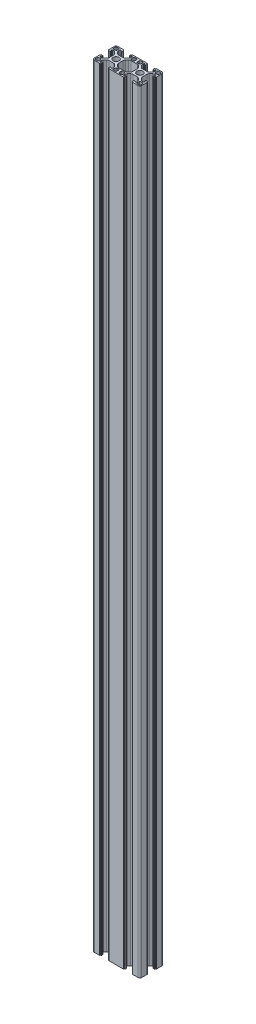
SolidWorks part; units mm, degrees
ref_plane "Спереди" through (0, 0, 0) normal (0, 0, 1) x (1, 0, 0)
ref_plane "Сверху" through (0, 0, 0) normal (0, 1, 0) x (1, 0, 0)
ref_plane "Справа" through (0, 0, 0) normal (1, 0, 0) x (0, 0, -1)
sketch "Эскиз1" plane through (0, 0, 0) normal (0, 1, 0) x (1, 0, 0)
  line L0 (-3.1522, 8.2837) -> (-1.6522, 6.7837) construction
  line L1 (18.3478, 9.7837) -> (15.3478, 6.7837) construction
  line L2 (-10.7522, 0.6837) -> (-0.7522, 10.6837) construction
  line L3 (9.2478, 4.6837) -> (11.1466, 4.6837)
  line L4 (9.2478, 0.6837) -> (19.2478, 10.6837) construction
  line L5 (16.8478, 8.2837) -> (15.3478, 9.7837) construction
  line L6 (12.5608, 5.2695) -> (13.862, 6.5707)
  line L7 (16.1478, 6.7837) -> (17.5478, 6.7837)
  line L8 (15.3478, 7.5837) -> (15.3478, 8.9837)
  line L9 (17.5478, 9.7837) -> (16.1478, 9.7837)
  line L10 (14.4478, 8.8837) -> (14.4478, 7.9849)
  line L11 (13.011, 8.757) -> (13.4914, 9.2373)
  line L12 (12.4478, 10.2328) -> (12.9478, 10.2328)
  line L13 (12.8343, 8.6837) -> (12.5478, 8.6837)
  line L14 (13.8449, 9.3837) -> (13.9478, 9.3837)
  line L15 (12.9478, 10.5337) -> (12.9478, 10.2328)
  line L16 (12.2978, 10.0828) -> (12.2978, 8.9337)
  line L17 (17.7478, 10.6837) -> (13.0978, 10.6837)
  line L18 (18.3478, 8.9837) -> (18.3478, 7.5837)
  line L19 (19.2478, 9.1837) -> (19.2478, 4.5337)
  line L20 (18.6469, 3.7337) -> (17.4978, 3.7337)
  line L21 (19.0978, 4.3837) -> (18.7969, 4.3837)
  line L22 (17.9478, 5.2808) -> (17.9478, 5.3837)
  line L23 (17.2478, 4.2702) -> (17.2478, 3.9837)
  line L24 (18.7969, 3.8837) -> (18.7969, 4.3837)
  line L25 (17.321, 4.447) -> (17.8014, 4.9273)
  line L26 (17.4478, 5.8837) -> (16.549, 5.8837)
  line L27 (13.8336, 3.9967) -> (15.1348, 5.2979)
  line L28 (13.2478, 0.6837) -> (13.2478, 2.5825)
  line L29 (13.2478, 0.6837) -> (13.2478, -1.2151)
  line L30 (13.8336, -2.6293) -> (15.1348, -3.9305)
  line L31 (15.3478, -6.2163) -> (15.3478, -7.6163)
  line L32 (16.1478, -5.4163) -> (17.5478, -5.4163)
  line L33 (18.3478, -7.6163) -> (18.3478, -6.2163)
  line L34 (17.4478, -4.5163) -> (16.549, -4.5163)
  line L35 (17.321, -3.0795) -> (17.8014, -3.5598)
  line L36 (18.7969, -2.5163) -> (18.7969, -3.0163)
  line L37 (17.2478, -2.9027) -> (17.2478, -2.6163)
  line L38 (17.9478, -3.9134) -> (17.9478, -4.0163)
  line L39 (19.0978, -3.0163) -> (18.7969, -3.0163)
  line L40 (18.6469, -2.3663) -> (17.4978, -2.3663)
  line L41 (19.2478, -7.8163) -> (19.2478, -3.1663)
  line L42 (17.5478, -8.4163) -> (16.1478, -8.4163)
  line L43 (17.7478, -9.3163) -> (13.0978, -9.3163)
  line L44 (12.2978, -8.7153) -> (12.2978, -7.5663)
  line L45 (12.9478, -9.1663) -> (12.9478, -8.8653)
  line L46 (13.8449, -8.0163) -> (13.9478, -8.0163)
  line L47 (12.8343, -7.3163) -> (12.5478, -7.3163)
  line L48 (12.4478, -8.8653) -> (12.9478, -8.8653)
  line L49 (13.011, -7.3895) -> (13.4914, -7.8698)
  line L50 (14.4478, -7.5163) -> (14.4478, -6.6175)
  line L51 (12.5608, -3.9021) -> (13.862, -5.2033)
  line L52 (9.2478, -3.3163) -> (11.1466, -3.3163)
  line L53 (18.3478, -8.4163) -> (15.3478, -5.4163) construction
  line L54 (9.2478, 0.6837) -> (19.2478, -9.3163) construction
  line L55 (16.8478, -6.9163) -> (18.3478, -5.4163) construction
  line L56 (9.2478, -3.3163) -> (7.349, -3.3163)
  line L57 (5.9348, -3.9021) -> (4.6336, -5.2033)
  line L58 (2.3478, -5.4163) -> (0.9478, -5.4163)
  line L59 (3.1478, -6.2163) -> (3.1478, -7.6163)
  line L60 (0.9478, -8.4163) -> (2.3478, -8.4163)
  line L61 (4.0478, -7.5163) -> (4.0478, -6.6175)
  line L62 (5.4846, -7.3895) -> (5.0043, -7.8698)
  line L63 (6.0478, -8.8653) -> (5.5478, -8.8653)
  line L64 (5.6614, -7.3163) -> (5.9478, -7.3163)
  line L65 (4.6507, -8.0163) -> (4.5478, -8.0163)
  line L66 (5.5478, -9.1663) -> (5.5478, -8.8653)
  line L67 (6.1978, -8.7153) -> (6.1978, -7.5663)
  line L68 (0.7478, -9.3163) -> (5.3978, -9.3163)
  line L69 (0.1478, -7.6163) -> (0.1478, -6.2163)
  line L70 (1.0478, -4.5163) -> (1.9466, -4.5163)
  line L71 (4.662, -2.6293) -> (3.3608, -3.9305)
  line L72 (5.2478, 0.6837) -> (5.2478, -1.2151)
  line L73 (-1.6522, 9.7837) -> (-4.6522, 6.7837) construction
  line L74 (0.1478, -8.4163) -> (3.1478, -5.4163) construction
  line L75 (-3.1522, -6.9163) -> (-4.6522, -8.4163) construction
  line L76 (9.2478, 0.6837) -> (-0.7522, -9.3163) construction
  line L77 (1.6478, -6.9163) -> (3.1478, -8.4163) construction
  line L78 (5.2478, 0.6837) -> (5.2478, 2.5825)
  line L79 (4.662, 3.9967) -> (3.3608, 5.2979)
  line L80 (3.1478, 7.5837) -> (3.1478, 8.9837)
  line L81 (2.3478, 6.7837) -> (0.9478, 6.7837)
  line L82 (0.1478, 8.9837) -> (0.1478, 7.5837)
  line L83 (1.0478, 5.8837) -> (1.9466, 5.8837)
  line L84 (0.9478, 9.7837) -> (2.3478, 9.7837)
  line L85 (0.7478, 10.6837) -> (5.3978, 10.6837)
  line L86 (6.1978, 10.0828) -> (6.1978, 8.9337)
  line L87 (5.5478, 10.5337) -> (5.5478, 10.2328)
  line L88 (4.6507, 9.3837) -> (4.5478, 9.3837)
  line L89 (5.6614, 8.6837) -> (5.9478, 8.6837)
  line L90 (6.0478, 10.2328) -> (5.5478, 10.2328)
  line L91 (5.4846, 8.757) -> (5.0043, 9.2373)
  line L92 (4.0478, 8.8837) -> (4.0478, 7.9849)
  line L93 (5.9348, 5.2695) -> (4.6336, 6.5707)
  line L94 (9.2478, 4.6837) -> (7.349, 4.6837)
  line L95 (-2.5162, 0.6837) -> (20.7522, 0.6837) construction
  line L96 (0.1478, 9.7837) -> (3.1478, 6.7837) construction
  line L97 (9.2478, -11.4027) -> (9.2478, 11.4027) construction
  line L98 (9.2478, 0.6837) -> (-0.7522, 10.6837) construction
  line L99 (1.6478, 8.2837) -> (0.1478, 6.7837) construction
  line L100 (-10.7522, 0.6837) -> (-0.7522, -9.3163) construction
  line L101 (-1.6522, -8.4163) -> (-4.6522, -5.4163) construction
  line L102 (-18.3522, -6.9163) -> (-19.8522, -5.4163) construction
  line L103 (-10.7522, 0.6837) -> (-20.7522, -9.3163) construction
  line L104 (-19.8522, -8.4163) -> (-16.8522, -5.4163) construction
  line L105 (-18.3522, 8.2837) -> (-16.8522, 9.7837) construction
  line L106 (-10.7522, 0.6837) -> (-20.7522, 10.6837) construction
  line L107 (-19.8522, 9.7837) -> (-16.8522, 6.7837) construction
  line L108 (-10.7522, 4.6837) -> (-8.8534, 4.6837)
  line L109 (-7.4392, 5.2695) -> (-6.138, 6.5707)
  line L110 (-5.5522, 8.8837) -> (-5.5522, 7.9849)
  line L111 (-6.989, 8.757) -> (-6.5086, 9.2373)
  line L112 (-7.5522, 10.2328) -> (-7.0522, 10.2328)
  line L113 (-7.1657, 8.6837) -> (-7.4522, 8.6837)
  line L114 (-6.1551, 9.3837) -> (-6.0522, 9.3837)
  line L115 (-7.0522, 10.5337) -> (-7.0522, 10.2328)
  line L116 (-7.7022, 10.0828) -> (-7.7022, 8.9337)
  line L117 (-2.2522, 10.6837) -> (-6.9022, 10.6837)
  line L118 (-2.4522, 9.7837) -> (-3.8522, 9.7837)
  line L119 (-2.5522, 5.8837) -> (-3.451, 5.8837)
  line L120 (-1.6522, 8.9837) -> (-1.6522, 7.5837)
  line L121 (-3.8522, 6.7837) -> (-2.4522, 6.7837)
  line L122 (-4.6522, 7.5837) -> (-4.6522, 8.9837)
  line L123 (-6.1664, 3.9967) -> (-4.8652, 5.2979)
  line L124 (-6.7522, 0.6837) -> (-6.7522, 2.5825)
  line L125 (-6.7522, 0.6837) -> (-6.7522, -1.2151)
  line L126 (-6.1664, -2.6293) -> (-4.8652, -3.9305)
  line L127 (-2.5522, -4.5163) -> (-3.451, -4.5163)
  line L128 (-1.6522, -7.6163) -> (-1.6522, -6.2163)
  line L129 (-2.2522, -9.3163) -> (-6.9022, -9.3163)
  line L130 (-7.7022, -8.7153) -> (-7.7022, -7.5663)
  line L131 (-7.0522, -9.1663) -> (-7.0522, -8.8653)
  line L132 (-6.1551, -8.0163) -> (-6.0522, -8.0163)
  line L133 (-7.1657, -7.3163) -> (-7.4522, -7.3163)
  line L134 (-7.5522, -8.8653) -> (-7.0522, -8.8653)
  line L135 (-6.989, -7.3895) -> (-6.5086, -7.8698)
  line L136 (-5.5522, -7.5163) -> (-5.5522, -6.6175)
  line L137 (-2.4522, -8.4163) -> (-3.8522, -8.4163)
  line L138 (-4.6522, -6.2163) -> (-4.6522, -7.6163)
  line L139 (-3.8522, -5.4163) -> (-2.4522, -5.4163)
  line L140 (-7.4392, -3.9021) -> (-6.138, -5.2033)
  line L141 (-10.7522, -3.3163) -> (-8.8534, -3.3163)
  line L142 (-10.7522, -3.3163) -> (-12.651, -3.3163)
  line L143 (-14.0652, -3.9021) -> (-15.3664, -5.2033)
  line L144 (-15.9522, -7.5163) -> (-15.9522, -6.6175)
  line L145 (-14.5154, -7.3895) -> (-14.9957, -7.8698)
  line L146 (-13.9522, -8.8653) -> (-14.4522, -8.8653)
  line L147 (-14.3386, -7.3163) -> (-14.0522, -7.3163)
  line L148 (-15.3493, -8.0163) -> (-15.4522, -8.0163)
  line L149 (-14.4522, -9.1663) -> (-14.4522, -8.8653)
  line L150 (-13.8022, -8.7153) -> (-13.8022, -7.5663)
  line L151 (-19.2522, -9.3163) -> (-14.6022, -9.3163)
  line L152 (-19.0522, -8.4163) -> (-17.6522, -8.4163)
  line L153 (-20.7522, -7.8163) -> (-20.7522, -3.1663)
  line L154 (-20.1512, -2.3663) -> (-19.0022, -2.3663)
  line L155 (-20.6022, -3.0163) -> (-20.3012, -3.0163)
  line L156 (-19.4522, -3.9134) -> (-19.4522, -4.0163)
  line L157 (-18.7522, -2.9027) -> (-18.7522, -2.6163)
  line L158 (-20.3012, -2.5163) -> (-20.3012, -3.0163)
  line L159 (-18.8254, -3.0795) -> (-19.3057, -3.5598)
  line L160 (-18.9522, -4.5163) -> (-18.0534, -4.5163)
  line L161 (-19.8522, -7.6163) -> (-19.8522, -6.2163)
  line L162 (-17.6522, -5.4163) -> (-19.0522, -5.4163)
  line L163 (-16.8522, -6.2163) -> (-16.8522, -7.6163)
  line L164 (-15.338, -2.6293) -> (-16.6392, -3.9305)
  line L165 (-14.7522, 0.6837) -> (-14.7522, -1.2151)
  line L166 (-14.7522, 0.6837) -> (-14.7522, 2.5825)
  line L167 (-15.338, 3.9967) -> (-16.6392, 5.2979)
  line L168 (-18.9522, 5.8837) -> (-18.0534, 5.8837)
  line L169 (-18.8254, 4.447) -> (-19.3057, 4.9273)
  line L170 (-20.3012, 3.8837) -> (-20.3012, 4.3837)
  line L171 (-18.7522, 4.2702) -> (-18.7522, 3.9837)
  line L172 (-19.4522, 5.2808) -> (-19.4522, 5.3837)
  line L173 (-20.6022, 4.3837) -> (-20.3012, 4.3837)
  line L174 (-20.1512, 3.7337) -> (-19.0022, 3.7337)
  line L175 (-20.7522, 9.1837) -> (-20.7522, 4.5337)
  line L176 (-19.8522, 8.9837) -> (-19.8522, 7.5837)
  line L177 (-19.2522, 10.6837) -> (-14.6022, 10.6837)
  line L178 (-13.8022, 10.0828) -> (-13.8022, 8.9337)
  line L179 (-14.4522, 10.5337) -> (-14.4522, 10.2328)
  line L180 (-15.3493, 9.3837) -> (-15.4522, 9.3837)
  line L181 (-14.3386, 8.6837) -> (-14.0522, 8.6837)
  line L182 (-13.9522, 10.2328) -> (-14.4522, 10.2328)
  line L183 (-14.5154, 8.757) -> (-14.9957, 9.2373)
  line L184 (-15.9522, 8.8837) -> (-15.9522, 7.9849)
  line L185 (-19.0522, 9.7837) -> (-17.6522, 9.7837)
  line L186 (-16.8522, 7.5837) -> (-16.8522, 8.9837)
  line L187 (-17.6522, 6.7837) -> (-19.0522, 6.7837)
  line L188 (-14.0652, 5.2695) -> (-15.3664, 6.5707)
  line L189 (-10.7522, 4.6837) -> (-12.651, 4.6837)
  line L190 (-2.2522, -9.3163) -> (0.7478, -9.3163)
  line L191 (-2.5522, -4.5163) -> (1.0478, -4.5163)
  line L192 (-2.5522, 5.8837) -> (1.0478, 5.8837)
  line L193 (-2.2522, 10.6837) -> (0.7478, 10.6837)
  arc A0 (18.3478, 8.9837) -> (17.5478, 9.7837) centre (17.5478, 8.9837) ccw
  arc A1 (16.1478, 9.7837) -> (15.3478, 8.9837) centre (16.1478, 8.9837) ccw
  arc A2 (16.1478, 6.7837) -> (15.3478, 7.5837) centre (16.1478, 7.5837) cw
  arc A3 (17.7478, 10.6837) -> (19.2478, 9.1837) centre (17.7478, 9.1837) cw
  arc A4 (12.4478, 10.2328) -> (12.2978, 10.0828) centre (12.4478, 10.0828) ccw
  arc A5 (13.0978, 10.6837) -> (12.9478, 10.5337) centre (13.0978, 10.5337) ccw
  arc A6 (12.8343, 8.6837) -> (13.011, 8.757) centre (12.8343, 8.9337) ccw
  arc A7 (12.5478, 8.6837) -> (12.2978, 8.9337) centre (12.5478, 8.9337) cw
  arc A8 (13.4914, 9.2373) -> (13.8449, 9.3837) centre (13.8449, 8.8837) cw
  arc A9 (13.9478, 9.3837) -> (14.4478, 8.8837) centre (13.9478, 8.8837) cw
  arc A10 (11.7478, 0.6837) -> (9.2478, 3.1837) centre (9.2478, 0.6837) ccw
  arc A11 (11.1466, 4.6837) -> (12.5608, 5.2695) centre (11.1466, 6.6837) ccw
  arc A12 (14.4478, 7.9849) -> (13.862, 6.5707) centre (12.4478, 7.9849) cw
  arc A13 (18.3478, 7.5837) -> (17.5478, 6.7837) centre (17.5478, 7.5837) cw
  arc A14 (17.9478, 5.3837) -> (17.4478, 5.8837) centre (17.4478, 5.3837) ccw
  arc A15 (17.8014, 4.9273) -> (17.9478, 5.2808) centre (17.4478, 5.2808) ccw
  arc A16 (17.2478, 3.9837) -> (17.4978, 3.7337) centre (17.4978, 3.9837) ccw
  arc A17 (17.2478, 4.2702) -> (17.321, 4.447) centre (17.4978, 4.2702) cw
  arc A18 (19.2478, 4.5337) -> (19.0978, 4.3837) centre (19.0978, 4.5337) cw
  arc A19 (18.7969, 3.8837) -> (18.6469, 3.7337) centre (18.6469, 3.8837) cw
  arc A20 (16.549, 5.8837) -> (15.1348, 5.2979) centre (16.549, 3.8837) ccw
  arc A21 (13.2478, 2.5825) -> (13.8336, 3.9967) centre (15.2478, 2.5825) cw
  arc A22 (17.5478, -8.4163) -> (18.3478, -7.6163) centre (17.5478, -7.6163) ccw
  arc A23 (18.3478, -6.2163) -> (17.5478, -5.4163) centre (17.5478, -6.2163) ccw
  arc A24 (15.3478, -6.2163) -> (16.1478, -5.4163) centre (16.1478, -6.2163) cw
  arc A25 (19.2478, -7.8163) -> (17.7478, -9.3163) centre (17.7478, -7.8163) cw
  arc A26 (18.7969, -2.5163) -> (18.6469, -2.3663) centre (18.6469, -2.5163) ccw
  arc A27 (19.2478, -3.1663) -> (19.0978, -3.0163) centre (19.0978, -3.1663) ccw
  arc A28 (17.2478, -2.9027) -> (17.321, -3.0795) centre (17.4978, -2.9027) ccw
  arc A29 (17.2478, -2.6163) -> (17.4978, -2.3663) centre (17.4978, -2.6163) cw
  arc A30 (17.8014, -3.5598) -> (17.9478, -3.9134) centre (17.4478, -3.9134) cw
  arc A31 (17.9478, -4.0163) -> (17.4478, -4.5163) centre (17.4478, -4.0163) cw
  arc A32 (9.2478, -1.8163) -> (11.7478, 0.6837) centre (9.2478, 0.6837) ccw
  arc A33 (13.2478, -1.2151) -> (13.8336, -2.6293) centre (15.2478, -1.2151) ccw
  arc A34 (16.549, -4.5163) -> (15.1348, -3.9305) centre (16.549, -2.5163) cw
  arc A35 (16.1478, -8.4163) -> (15.3478, -7.6163) centre (16.1478, -7.6163) cw
  arc A36 (13.9478, -8.0163) -> (14.4478, -7.5163) centre (13.9478, -7.5163) ccw
  arc A37 (13.4914, -7.8698) -> (13.8449, -8.0163) centre (13.8449, -7.5163) ccw
  arc A38 (12.5478, -7.3163) -> (12.2978, -7.5663) centre (12.5478, -7.5663) ccw
  arc A39 (12.8343, -7.3163) -> (13.011, -7.3895) centre (12.8343, -7.5663) cw
  arc A40 (13.0978, -9.3163) -> (12.9478, -9.1663) centre (13.0978, -9.1663) cw
  arc A41 (12.4478, -8.8653) -> (12.2978, -8.7153) centre (12.4478, -8.7153) cw
  arc A42 (14.4478, -6.6175) -> (13.862, -5.2033) centre (12.4478, -6.6175) ccw
  arc A43 (11.1466, -3.3163) -> (12.5608, -3.9021) centre (11.1466, -5.3163) cw
  arc A44 (0.1478, -7.6163) -> (0.9478, -8.4163) centre (0.9478, -7.6163) ccw
  arc A45 (2.3478, -8.4163) -> (3.1478, -7.6163) centre (2.3478, -7.6163) ccw
  arc A46 (2.3478, -5.4163) -> (3.1478, -6.2163) centre (2.3478, -6.2163) cw
  arc A47 (6.0478, -8.8653) -> (6.1978, -8.7153) centre (6.0478, -8.7153) ccw
  arc A48 (5.3978, -9.3163) -> (5.5478, -9.1663) centre (5.3978, -9.1663) ccw
  arc A49 (5.6614, -7.3163) -> (5.4846, -7.3895) centre (5.6614, -7.5663) ccw
  arc A50 (5.9478, -7.3163) -> (6.1978, -7.5663) centre (5.9478, -7.5663) cw
  arc A51 (5.0043, -7.8698) -> (4.6507, -8.0163) centre (4.6507, -7.5163) cw
  arc A52 (4.5478, -8.0163) -> (4.0478, -7.5163) centre (4.5478, -7.5163) cw
  arc A53 (6.7478, 0.6837) -> (9.2478, -1.8163) centre (9.2478, 0.6837) ccw
  arc A54 (7.349, -3.3163) -> (5.9348, -3.9021) centre (7.349, -5.3163) ccw
  arc A55 (4.0478, -6.6175) -> (4.6336, -5.2033) centre (6.0478, -6.6175) cw
  arc A56 (0.1478, -6.2163) -> (0.9478, -5.4163) centre (0.9478, -6.2163) cw
  arc A57 (1.9466, -4.5163) -> (3.3608, -3.9305) centre (1.9466, -2.5163) ccw
  arc A58 (5.2478, -1.2151) -> (4.662, -2.6293) centre (3.2478, -1.2151) cw
  arc A59 (0.9478, 9.7837) -> (0.1478, 8.9837) centre (0.9478, 8.9837) ccw
  arc A60 (0.1478, 7.5837) -> (0.9478, 6.7837) centre (0.9478, 7.5837) ccw
  arc A61 (3.1478, 7.5837) -> (2.3478, 6.7837) centre (2.3478, 7.5837) cw
  arc A62 (9.2478, 3.1837) -> (6.7478, 0.6837) centre (9.2478, 0.6837) ccw
  arc A63 (5.2478, 2.5825) -> (4.662, 3.9967) centre (3.2478, 2.5825) ccw
  arc A64 (1.9466, 5.8837) -> (3.3608, 5.2979) centre (1.9466, 3.8837) cw
  arc A65 (2.3478, 9.7837) -> (3.1478, 8.9837) centre (2.3478, 8.9837) cw
  arc A66 (4.5478, 9.3837) -> (4.0478, 8.8837) centre (4.5478, 8.8837) ccw
  arc A67 (5.0043, 9.2373) -> (4.6507, 9.3837) centre (4.6507, 8.8837) ccw
  arc A68 (5.9478, 8.6837) -> (6.1978, 8.9337) centre (5.9478, 8.9337) ccw
  arc A69 (5.6614, 8.6837) -> (5.4846, 8.757) centre (5.6614, 8.9337) cw
  arc A70 (5.3978, 10.6837) -> (5.5478, 10.5337) centre (5.3978, 10.5337) cw
  arc A71 (6.0478, 10.2328) -> (6.1978, 10.0828) centre (6.0478, 10.0828) cw
  arc A72 (4.0478, 7.9849) -> (4.6336, 6.5707) centre (6.0478, 7.9849) ccw
  arc A73 (7.349, 4.6837) -> (5.9348, 5.2695) centre (7.349, 6.6837) cw
  arc A74 (-8.8534, 4.6837) -> (-7.4392, 5.2695) centre (-8.8534, 6.6837) ccw
  arc A75 (-5.5522, 7.9849) -> (-6.138, 6.5707) centre (-7.5522, 7.9849) cw
  arc A76 (-7.5522, 10.2328) -> (-7.7022, 10.0828) centre (-7.5522, 10.0828) ccw
  arc A77 (-6.9022, 10.6837) -> (-7.0522, 10.5337) centre (-6.9022, 10.5337) ccw
  arc A78 (-7.1657, 8.6837) -> (-6.989, 8.757) centre (-7.1657, 8.9337) ccw
  arc A79 (-7.4522, 8.6837) -> (-7.7022, 8.9337) centre (-7.4522, 8.9337) cw
  arc A80 (-6.5086, 9.2373) -> (-6.1551, 9.3837) centre (-6.1551, 8.8837) cw
  arc A81 (-6.0522, 9.3837) -> (-5.5522, 8.8837) centre (-6.0522, 8.8837) cw
  arc A82 (-3.8522, 9.7837) -> (-4.6522, 8.9837) centre (-3.8522, 8.9837) ccw
  arc A83 (-3.451, 5.8837) -> (-4.8652, 5.2979) centre (-3.451, 3.8837) ccw
  arc A84 (-6.7522, 2.5825) -> (-6.1664, 3.9967) centre (-4.7522, 2.5825) cw
  arc A85 (-10.7522, 3.1837) -> (-8.2522, 0.6837) centre (-10.7522, 0.6837) cw
  arc A86 (-4.6522, 7.5837) -> (-3.8522, 6.7837) centre (-3.8522, 7.5837) ccw
  arc A87 (-1.6522, 7.5837) -> (-2.4522, 6.7837) centre (-2.4522, 7.5837) cw
  arc A88 (-2.4522, 9.7837) -> (-1.6522, 8.9837) centre (-2.4522, 8.9837) cw
  arc A89 (-6.7522, -1.2151) -> (-6.1664, -2.6293) centre (-4.7522, -1.2151) ccw
  arc A90 (-3.451, -4.5163) -> (-4.8652, -3.9305) centre (-3.451, -2.5163) cw
  arc A91 (-1.6522, -6.2163) -> (-2.4522, -5.4163) centre (-2.4522, -6.2163) ccw
  arc A92 (-5.5522, -6.6175) -> (-6.138, -5.2033) centre (-7.5522, -6.6175) ccw
  arc A93 (-8.8534, -3.3163) -> (-7.4392, -3.9021) centre (-8.8534, -5.3163) cw
  arc A94 (-8.2522, 0.6837) -> (-10.7522, -1.8163) centre (-10.7522, 0.6837) cw
  arc A95 (-6.0522, -8.0163) -> (-5.5522, -7.5163) centre (-6.0522, -7.5163) ccw
  arc A96 (-6.5086, -7.8698) -> (-6.1551, -8.0163) centre (-6.1551, -7.5163) ccw
  arc A97 (-7.4522, -7.3163) -> (-7.7022, -7.5663) centre (-7.4522, -7.5663) ccw
  arc A98 (-7.1657, -7.3163) -> (-6.989, -7.3895) centre (-7.1657, -7.5663) cw
  arc A99 (-6.9022, -9.3163) -> (-7.0522, -9.1663) centre (-6.9022, -9.1663) cw
  arc A100 (-7.5522, -8.8653) -> (-7.7022, -8.7153) centre (-7.5522, -8.7153) cw
  arc A101 (-3.8522, -5.4163) -> (-4.6522, -6.2163) centre (-3.8522, -6.2163) ccw
  arc A102 (-3.8522, -8.4163) -> (-4.6522, -7.6163) centre (-3.8522, -7.6163) cw
  arc A103 (-1.6522, -7.6163) -> (-2.4522, -8.4163) centre (-2.4522, -7.6163) cw
  arc A104 (-12.651, -3.3163) -> (-14.0652, -3.9021) centre (-12.651, -5.3163) ccw
  arc A105 (-15.9522, -6.6175) -> (-15.3664, -5.2033) centre (-13.9522, -6.6175) cw
  arc A106 (-13.9522, -8.8653) -> (-13.8022, -8.7153) centre (-13.9522, -8.7153) ccw
  arc A107 (-14.6022, -9.3163) -> (-14.4522, -9.1663) centre (-14.6022, -9.1663) ccw
  arc A108 (-14.3386, -7.3163) -> (-14.5154, -7.3895) centre (-14.3386, -7.5663) ccw
  arc A109 (-14.0522, -7.3163) -> (-13.8022, -7.5663) centre (-14.0522, -7.5663) cw
  arc A110 (-14.9957, -7.8698) -> (-15.3493, -8.0163) centre (-15.3493, -7.5163) cw
  arc A111 (-15.4522, -8.0163) -> (-15.9522, -7.5163) centre (-15.4522, -7.5163) cw
  arc A112 (-17.6522, -8.4163) -> (-16.8522, -7.6163) centre (-17.6522, -7.6163) ccw
  arc A113 (-18.0534, -4.5163) -> (-16.6392, -3.9305) centre (-18.0534, -2.5163) ccw
  arc A114 (-14.7522, -1.2151) -> (-15.338, -2.6293) centre (-16.7522, -1.2151) cw
  arc A115 (-10.7522, -1.8163) -> (-13.2522, 0.6837) centre (-10.7522, 0.6837) cw
  arc A116 (-19.4522, -4.0163) -> (-18.9522, -4.5163) centre (-18.9522, -4.0163) ccw
  arc A117 (-19.3057, -3.5598) -> (-19.4522, -3.9134) centre (-18.9522, -3.9134) ccw
  arc A118 (-18.7522, -2.6163) -> (-19.0022, -2.3663) centre (-19.0022, -2.6163) ccw
  arc A119 (-18.7522, -2.9027) -> (-18.8254, -3.0795) centre (-19.0022, -2.9027) cw
  arc A120 (-20.7522, -3.1663) -> (-20.6022, -3.0163) centre (-20.6022, -3.1663) cw
  arc A121 (-20.3012, -2.5163) -> (-20.1512, -2.3663) centre (-20.1512, -2.5163) cw
  arc A122 (-20.7522, -7.8163) -> (-19.2522, -9.3163) centre (-19.2522, -7.8163) ccw
  arc A123 (-16.8522, -6.2163) -> (-17.6522, -5.4163) centre (-17.6522, -6.2163) ccw
  arc A124 (-19.8522, -6.2163) -> (-19.0522, -5.4163) centre (-19.0522, -6.2163) cw
  arc A125 (-19.0522, -8.4163) -> (-19.8522, -7.6163) centre (-19.0522, -7.6163) cw
  arc A126 (-14.7522, 2.5825) -> (-15.338, 3.9967) centre (-16.7522, 2.5825) ccw
  arc A127 (-18.0534, 5.8837) -> (-16.6392, 5.2979) centre (-18.0534, 3.8837) cw
  arc A128 (-20.3012, 3.8837) -> (-20.1512, 3.7337) centre (-20.1512, 3.8837) ccw
  arc A129 (-20.7522, 4.5337) -> (-20.6022, 4.3837) centre (-20.6022, 4.5337) ccw
  arc A130 (-18.7522, 4.2702) -> (-18.8254, 4.447) centre (-19.0022, 4.2702) ccw
  arc A131 (-18.7522, 3.9837) -> (-19.0022, 3.7337) centre (-19.0022, 3.9837) cw
  arc A132 (-19.3057, 4.9273) -> (-19.4522, 5.2808) centre (-18.9522, 5.2808) cw
  arc A133 (-19.4522, 5.3837) -> (-18.9522, 5.8837) centre (-18.9522, 5.3837) cw
  arc A134 (-19.8522, 7.5837) -> (-19.0522, 6.7837) centre (-19.0522, 7.5837) ccw
  arc A135 (-15.9522, 7.9849) -> (-15.3664, 6.5707) centre (-13.9522, 7.9849) ccw
  arc A136 (-12.651, 4.6837) -> (-14.0652, 5.2695) centre (-12.651, 6.6837) cw
  arc A137 (-13.2522, 0.6837) -> (-10.7522, 3.1837) centre (-10.7522, 0.6837) cw
  arc A138 (-15.4522, 9.3837) -> (-15.9522, 8.8837) centre (-15.4522, 8.8837) ccw
  arc A139 (-14.9957, 9.2373) -> (-15.3493, 9.3837) centre (-15.3493, 8.8837) ccw
  arc A140 (-14.0522, 8.6837) -> (-13.8022, 8.9337) centre (-14.0522, 8.9337) ccw
  arc A141 (-14.3386, 8.6837) -> (-14.5154, 8.757) centre (-14.3386, 8.9337) cw
  arc A142 (-14.6022, 10.6837) -> (-14.4522, 10.5337) centre (-14.6022, 10.5337) cw
  arc A143 (-13.9522, 10.2328) -> (-13.8022, 10.0828) centre (-13.9522, 10.0828) cw
  arc A144 (-19.2522, 10.6837) -> (-20.7522, 9.1837) centre (-19.2522, 9.1837) ccw
  arc A145 (-17.6522, 6.7837) -> (-16.8522, 7.5837) centre (-17.6522, 7.5837) ccw
  arc A146 (-17.6522, 9.7837) -> (-16.8522, 8.9837) centre (-17.6522, 8.9837) cw
  arc A147 (-19.8522, 8.9837) -> (-19.0522, 9.7837) centre (-19.0522, 8.9837) cw
  point P0 (9.2478, 0.6837)
  point P12 (9.2478, 0.6837)
  point P45 (17.9478, 4.3837)
  point P104 (12.9478, -8.0163)
  point P155 (12.9478, 9.3837)
  point P163 (17.9478, -3.0163)
  point P164 (9.2478, -3.2405)
  point P166 (9.2478, 0.6837)
  point P224 (5.5478, -8.0163)
  point P225 (5.3236, 0.6837)
  point P227 (9.2478, 0.6837)
  point P267 (5.5478, 9.3837)
  point P272 (13.1721, 0.6837)
  point P288 (9.2478, 4.608)
  point P290 (9.2478, 0.6837)
  point P515 (-10.7522, 4.608)
  point P516 (-14.6764, 0.6837)
  point P517 (-7.0522, 9.3837)
  point P518 (-6.8279, 0.6837)
  point P519 (-7.0522, -8.0163)
  point P520 (-10.7522, -3.2405)
  point P521 (-19.4522, -3.0163)
  point P522 (-14.4522, 9.3837)
  point P523 (-14.4522, -8.0163)
  point P524 (-19.4522, 4.3837)
extrude "Бобышка-Вытянуть1" add sketch "Эскиз1" along normal blind 650
